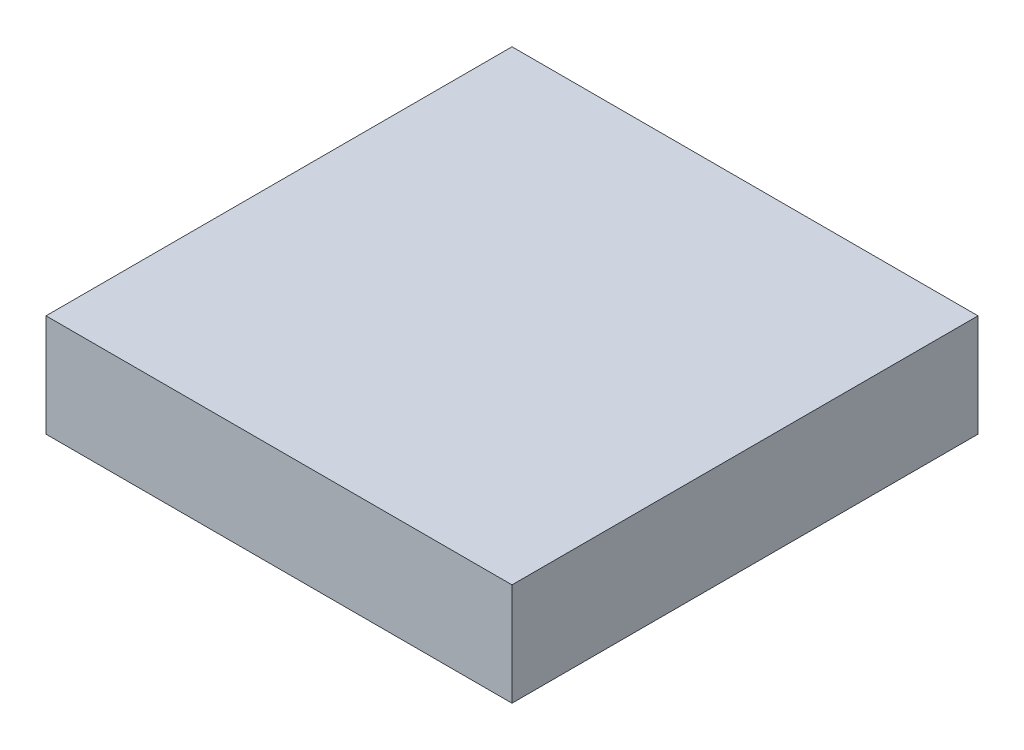
SolidWorks part; units mm, degrees
ref_plane "Front Plane" through (0, 0, 0) normal (0, 0, 1) x (1, 0, 0)
ref_plane "Top Plane" through (0, 0, 0) normal (0, 1, 0) x (1, 0, 0)
ref_plane "Right Plane" through (0, 0, 0) normal (1, 0, 0) x (0, 0, -1)
sketch "Sketch2" plane through (0, 0, 0) normal (0, 1, 0) x (1, 0, 0)
  line L1 (-12.7, -12.7) -> (12.7, -12.7)
  line L2 (-12.7, -12.7) -> (-12.7, 12.7)
  line L3 (-12.7, 12.7) -> (12.7, 12.7)
  line L4 (12.7, -12.7) -> (12.7, 12.7)
  line L5 (-12.7, -12.7) -> (12.7, 12.7) construction
  line L6 (-12.7, 12.7) -> (12.7, -12.7) construction
  point P0 (0, 0)
  dimension "D1" = 25.4
  dimension "D2" = 25.4
extrude "Boss-Extrude1" add sketch "Sketch2" along normal blind 5.588
